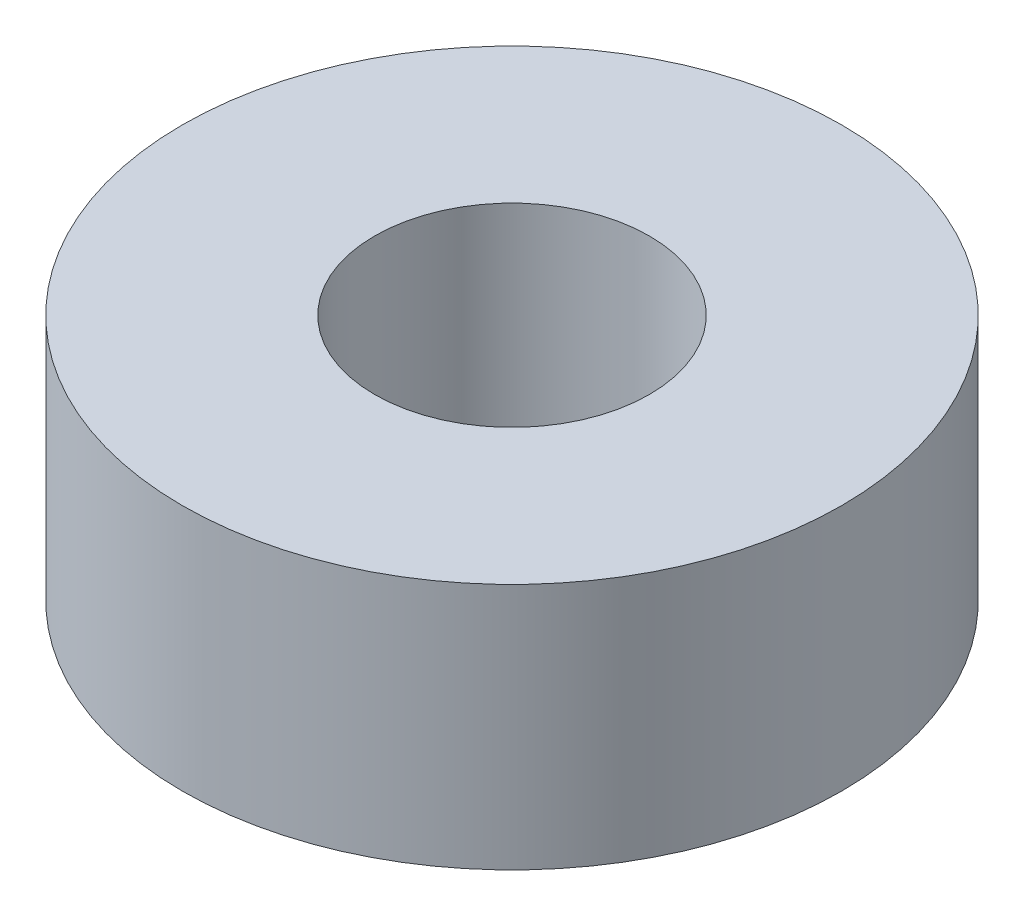
SolidWorks part; units mm, degrees
ref_plane "Front Plane" through (0, 0, 0) normal (0, 0, 1) x (1, 0, 0)
ref_plane "Top Plane" through (0, 0, 0) normal (0, 1, 0) x (1, 0, 0)
ref_plane "Right Plane" through (0, 0, 0) normal (1, 0, 0) x (0, 0, -1)
sketch "Sketch1" plane through (0, 0, 0) normal (0, 1, 0) x (1, 0, 0)
  circle A0 centre (0, 0) radius 6
  circle A1 centre (0, 0) radius 2.5
  dimension "D1" = 12
  dimension "D2" = 5
extrude "Boss-Extrude1" add sketch "Sketch1" along normal blind 4.5
equation "\"D1@Boss-Extrude1\"=3/8in"
